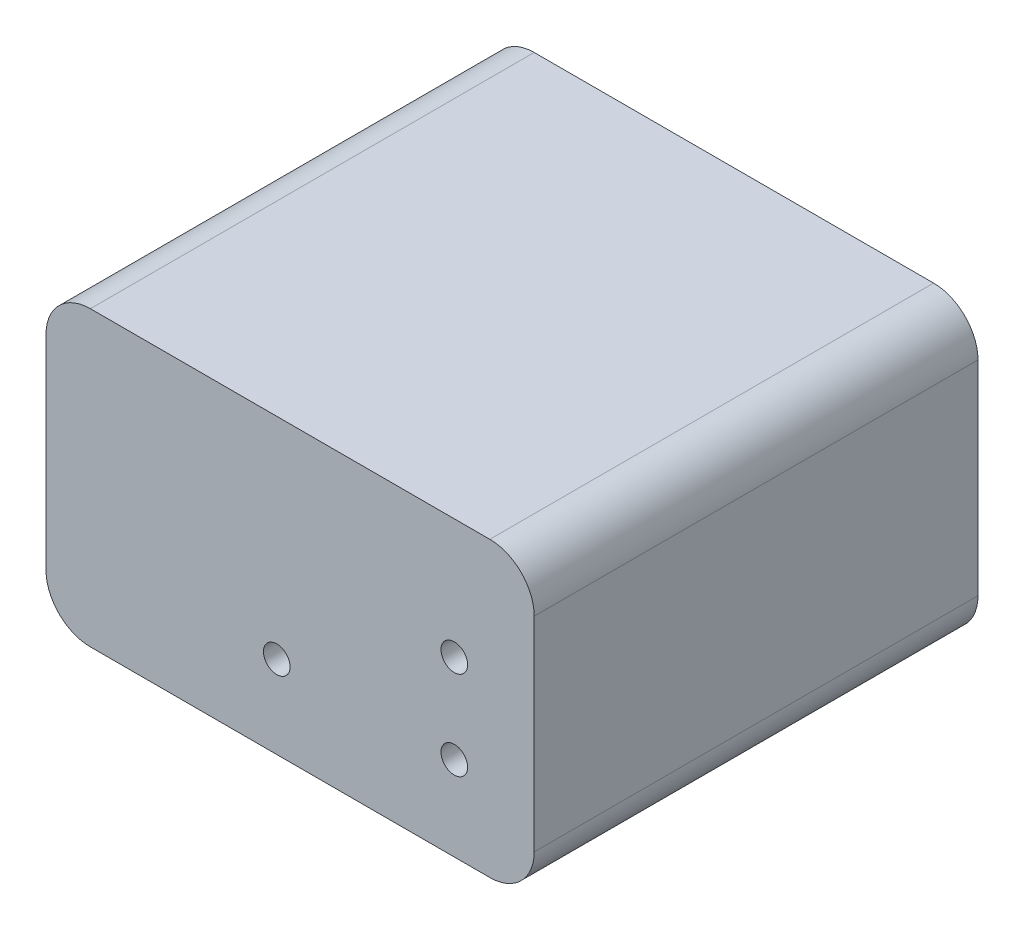
SolidWorks part; units mm, degrees
ref_plane "Plan de face" through (0, 0, 0) normal (0, 0, 1) x (1, 0, 0)
ref_plane "Plan de dessus" through (0, 0, 0) normal (0, 1, 0) x (1, 0, 0)
ref_plane "Plan de droite" through (0, 0, 0) normal (1, 0, 0) x (0, 0, -1)
sketch "Esquisse1" plane through (0, 0, 0) normal (0, 0, 1) x (1, 0, 0)
  line L1 (0, 0) -> (-55, 0)
  line L2 (0, 0) -> (0, 33)
  line L3 (0, 33) -> (-55, 33)
  line L4 (-55, 0) -> (-55, 33)
  dimension "D2" = 55
  dimension "D1" = 33
extrude "Boss.-Extru.1" add sketch "Esquisse1" along normal blind 50
sketch "Esquisse2" plane through (0, 0, 0) normal (0, 0, 1) x (1, 0, 0)
  line L6 (-39, 29) -> (-16, 29)
  line L7 (-39, 3) -> (-16, 3)
  line L8 (-55, 0) -> (0, 0) construction
  line L10 (0, 0) -> (0, 33) construction
  arc A3 (-39, 29) -> (-39, 3) centre (-39, 16) ccw
  arc A4 (-16, 3) -> (-16, 29) centre (-16, 16) ccw
  dimension "D3" = 3
  dimension "D7" = 16
  dimension "D5" = 23
  dimension "D6" = 26
extrude "Enlèv. mat.-Extru.2" cut sketch "Esquisse2" along normal blind 45
fillet "Congé1" radius 5 4 edges at (-55, 33, 25) (-55, 0, 25) (0, 0, 25) (0, 33, 25)
sketch "Esquisse3" plane through (0, 0, 50) normal (0, 0, 1) x (1, 0, 0)
  circle A0 centre (-29, 9.3) radius 1.5
  circle A1 centre (-9, 19.5) radius 1.5
  circle A3 centre (-9, 9.5) radius 1.5
  dimension "D1" = 3
  dimension "D2" = 3
  dimension "D3" = 3
extrude "Enlèv. mat.-Extru.3" cut sketch "Esquisse3" against normal blind 10
sketch "Esquisse4" plane through (0, 0, 45) normal (0, 0, -1) x (-1, 0, 0)
  line L0 (16, 29) -> (39, 29) construction
  line L1 (27.3546, 6.45) -> (30.6454, 6.45)
  line L2 (30.6454, 6.45) -> (32.2909, 9.3)
  line L3 (32.2909, 9.3) -> (30.6454, 12.15)
  line L4 (30.6454, 12.15) -> (27.3546, 12.15)
  line L5 (27.3546, 12.15) -> (25.7091, 9.3)
  line L6 (25.7091, 9.3) -> (27.3546, 6.45)
  line L7 (7.3546, 6.65) -> (10.6454, 6.65)
  line L8 (10.6454, 6.65) -> (12.2909, 9.5)
  line L9 (12.2909, 9.5) -> (10.6454, 12.35)
  line L10 (10.6454, 12.35) -> (7.3546, 12.35)
  line L11 (7.3546, 12.35) -> (5.7091, 9.5)
  line L12 (5.7091, 9.5) -> (7.3546, 6.65)
  line L13 (7.3546, 16.65) -> (10.6454, 16.65)
  line L14 (10.6454, 16.65) -> (12.2909, 19.5)
  line L15 (12.2909, 19.5) -> (10.6454, 22.35)
  line L16 (10.6454, 22.35) -> (7.3546, 22.35)
  line L17 (7.3546, 22.35) -> (5.7091, 19.5)
  line L18 (5.7091, 19.5) -> (7.3546, 16.65)
  circle A0 centre (29, 9.3) radius 2.85 construction
  circle A1 centre (9, 9.5) radius 2.85 construction
  circle A2 centre (9, 19.5) radius 2.85 construction
  point P19 (9, 6.65)
  point P28 (9, 22.35)
  dimension "D1" = 5.7
  dimension "D2" = 5.7
  dimension "D3" = 5.7
extrude "Enlèv. mat.-Extru.4" cut sketch "Esquisse4" against normal blind 2
